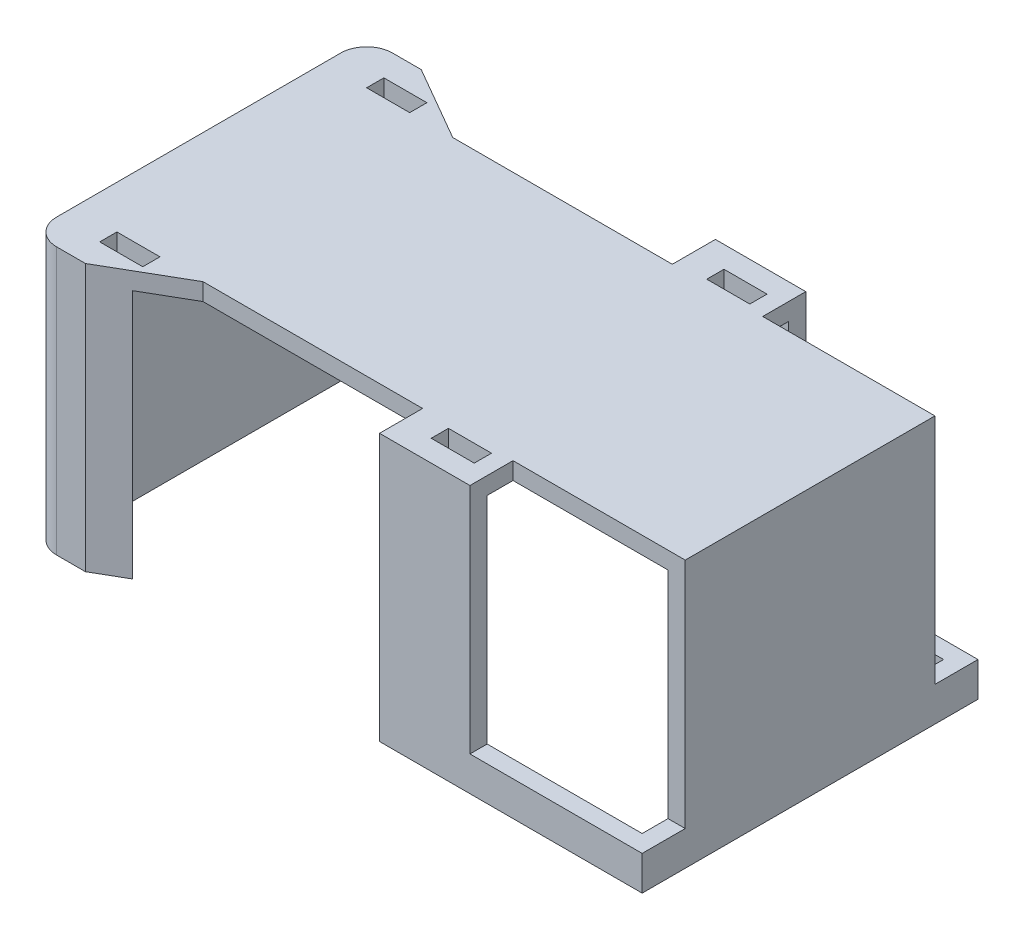
SolidWorks part; units mm, degrees
ref_plane "Front Plane" through (0, 0, 0) normal (0, 0, 1) x (1, 0, 0)
ref_plane "Top Plane" through (0, 0, 0) normal (0, 1, 0) x (1, 0, 0)
ref_plane "Right Plane" through (0, 0, 0) normal (1, 0, 0) x (0, 0, -1)
sketch "Sketch1" plane through (0, 0, 0) normal (0, 1, 0) x (1, 0, 0)
  line L1 (-35.5, 19.5) -> (35.5, 19.5)
  line L2 (-35.5, 19.5) -> (-35.5, -19.5)
  line L3 (-35.5, -19.5) -> (35.5, -19.5)
  line L4 (35.5, 19.5) -> (35.5, -19.5)
  line L5 (-35.5, 19.5) -> (35.5, -19.5) construction
  line L6 (-35.5, -19.5) -> (35.5, 19.5) construction
  point P0 (0, 0)
  dimension "D1" = 39
  dimension "D2" = 71
extrude "Boss-Extrude1" add sketch "Sketch1" along normal blind 31
shell "Shell1" thickness 2
sketch "Sketch2" plane through (0, 31, 0) normal (0, 1, 0) x (1, 0, 0)
  line L0 (0, 0) -> (35.5, 0) construction
  line L1 (35.5, -19.5) -> (35.5, 19.5) construction
  line L2 (35.5, 19.5) -> (-35.5, 19.5) construction
  line L3 (-29.1603, 19.5) -> (5, 19.5)
  line L4 (-29.1603, 19.5) -> (-20.5, 14.5)
  line L5 (-20.5, 14.5) -> (5, 14.5)
  line L6 (5, 19.5) -> (5, 14.5)
  line L7 (-20.5, -14.5) -> (5, -14.5)
  line L8 (5, -19.5) -> (5, -14.5)
  line L9 (-29.1603, -19.5) -> (5, -19.5)
  line L10 (-29.1603, -19.5) -> (-20.5, -14.5)
  line L11 (-35.5, 19.5) -> (-35.5, -19.5) construction
  dimension "D1" = 25.5
  dimension "D2" = 29
  dimension "D3" = 15
  dimension "D4" = 150
extrude "Cut-Extrude1" cut sketch "Sketch2" against normal through all
sketch "Sketch4" plane through (0, 31, -31) normal (0, -1, 0) x (1, 0, 0)
  line L0 (0, 31) -> (36, 31) construction
  line L3 (15.5, 50.5) -> (35.5, 50.5)
  line L4 (15.5, 50.5) -> (15.5, 45.5)
  line L5 (15.5, 45.5) -> (35.5, 45.5)
  line L6 (35.5, 50.5) -> (35.5, 45.5)
  line L7 (15.5, 16.5) -> (35.5, 16.5)
  line L8 (35.5, 11.5) -> (35.5, 16.5)
  line L9 (15.5, 11.5) -> (35.5, 11.5)
  line L10 (15.5, 11.5) -> (15.5, 16.5)
  line L12 (5, 50.5) -> (35.5, 50.5) construction
  line L13 (35.5, 11.5) -> (5, 11.5) construction
  line L14 (35.5, 50.5) -> (35.5, 11.5) construction
  dimension "D1" = 20
  dimension "D2" = 29
  dimension "D3" = 0
extrude "Cut-Extrude2" cut sketch "Sketch4" along normal blind 27
sketch "Sketch5" plane through (0, 31, 0) normal (0, 1, 0) x (1, 0, 0)
  line L0 (0, 0) -> (-35.5, 0) construction
  line L1 (-30.5, 16.5) -> (-25.5, 16.5)
  line L2 (-30.5, 16.5) -> (-30.5, 14.5)
  line L3 (-30.5, 14.5) -> (-25.5, 14.5)
  line L4 (-25.5, 16.5) -> (-25.5, 14.5)
  line L5 (-30.5, 16.5) -> (-25.5, 14.5) construction
  line L6 (-30.5, 14.5) -> (-25.5, 16.5) construction
  line L7 (8.5, 17) -> (13.5, 17)
  line L8 (8.5, 17) -> (8.5, 15)
  line L9 (8.5, 15) -> (13.5, 15)
  line L10 (13.5, 17) -> (13.5, 15)
  line L11 (8.5, 17) -> (13.5, 15) construction
  line L12 (8.5, 15) -> (13.5, 17) construction
  line L13 (-35.5, 19.5) -> (-35.5, -19.5) construction
  line L14 (8.5, -15) -> (13.5, -17) construction
  line L15 (8.5, -17) -> (13.5, -15) construction
  line L16 (13.5, -17) -> (13.5, -15)
  line L17 (8.5, -15) -> (13.5, -15)
  line L18 (8.5, -17) -> (8.5, -15)
  line L19 (8.5, -17) -> (13.5, -17)
  line L20 (-30.5, -14.5) -> (-25.5, -16.5) construction
  line L21 (-30.5, -16.5) -> (-25.5, -14.5) construction
  line L22 (-25.5, -16.5) -> (-25.5, -14.5)
  line L23 (-30.5, -14.5) -> (-25.5, -14.5)
  line L24 (-30.5, -16.5) -> (-30.5, -14.5)
  line L25 (-30.5, -16.5) -> (-25.5, -16.5)
  point P0 (-28, 15.5)
  point P5 (11, 16)
  point P19 (11, -16)
  point P24 (-28, -15.5)
  point P25 (13.5, 19.8572)
  dimension "D1" = 29
  dimension "D2" = 30
  dimension "D3" = 5
  dimension "D4" = 5
  dimension "D5" = 2
  dimension "D6" = 34
  dimension "D7" = 5
  dimension "D8" = 2
extrude "Cut-Extrude3" cut sketch "Sketch5" against normal through all
fillet "Fillet2" radius 3 2 edges at (-35.5, 15.5, -19.5) (-35.5, 15.5, 19.5)
